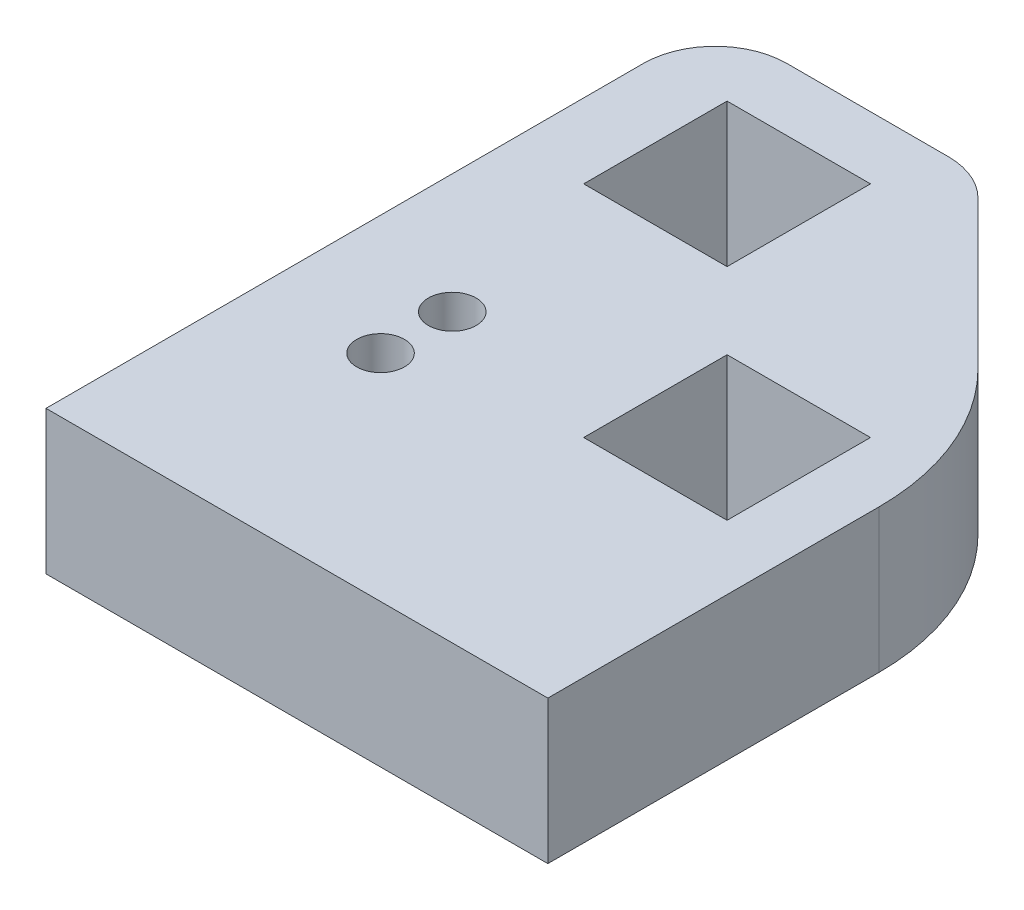
SolidWorks part; units mm, degrees
ref_plane "Front Plane" through (0, 0, 0) normal (0, 0, 1) x (1, 0, 0)
ref_plane "Top Plane" through (0, 0, 0) normal (0, 1, 0) x (1, 0, 0)
ref_plane "Right Plane" through (0, 0, 0) normal (1, 0, 0) x (0, 0, -1)
sketch "Sketch1" plane through (0, 0, 0) normal (0, 1, 0) x (1, 0, 0)
  line L0 (21, 0) -> (21, 9)
  line L1 (0, 0) -> (21, 0)
  line L2 (0, 0) -> (0, 28)
  line L3 (0, 28) -> (27, 28)
  line L4 (27, 9) -> (27, 28)
  line L5 (21, 9) -> (27, 9)
  dimension "D1" = 27
  dimension "D2" = 28
  dimension "D3" = 6
  dimension "D4" = 9
extrude "Boss-Extrude1" add sketch "Sketch1" along normal blind 6
sketch "Sketch2" plane through (0, 6, 0) normal (0, 1, 0) x (1, 0, 0)
  line L0 (-6.0122, 34.5122) -> (24, 4.5) construction
  line L1 (0, 0) -> (21, 0) construction
  line L2 (21, 0) -> (21, 9) construction
  line L4 (3.1152, 25.3848) -> (8.1152, 25.3848)
  line L5 (3.1152, 25.3848) -> (3.1152, 20.3848)
  line L6 (3.1152, 20.3848) -> (8.1152, 20.3848)
  line L7 (8.1152, 25.3848) -> (8.1152, 20.3848)
  line L8 (3.1152, 25.3848) -> (8.1152, 20.3848) construction
  line L9 (3.1152, 20.3848) -> (8.1152, 25.3848) construction
  line L10 (12.3076, 16.1924) -> (17.3076, 16.1924)
  line L11 (12.3076, 16.1924) -> (12.3076, 11.1924)
  line L12 (12.3076, 11.1924) -> (17.3076, 11.1924)
  line L13 (17.3076, 16.1924) -> (17.3076, 11.1924)
  line L14 (12.3076, 16.1924) -> (17.3076, 11.1924) construction
  line L15 (12.3076, 11.1924) -> (17.3076, 16.1924) construction
  point P6 (5.6152, 22.8848)
  point P11 (14.8076, 13.6924)
  dimension "D1" = 45
  dimension "D2" = 4.5
  dimension "D3" = 3
  dimension "D4" = 13
  dimension "D5" = 13
  dimension "D6" = 5
  dimension "D7" = 5
extrude "Cut-Extrude1" cut sketch "Sketch2" against normal through all
sketch "Sketch3" plane through (0, 6, 0) normal (0, 1, 0) x (1, 0, 0)
  line L0 (21, 18) -> (11, 28)
  line L1 (27, 28) -> (0, 28) construction
  line L2 (11, 28) -> (33.4367, 34.251)
  line L3 (33.4367, 34.251) -> (36.0805, 3.3835)
  line L4 (36.0805, 3.3835) -> (21, 9)
  line L5 (21, 9) -> (21, 18)
  dimension "D1" = 135
  dimension "D2" = 9
extrude "Cut-Extrude2" cut sketch "Sketch3" against normal through all
sketch "Sketch6" plane through (0, 6, 0) normal (0, 1, 0) x (1, 0, 0)
  line L1 (3.1152, 25.3848) -> (9.1152, 25.3848)
  line L2 (3.1152, 25.3848) -> (3.1152, 19.3848)
  line L3 (3.1152, 19.3848) -> (9.1152, 19.3848)
  line L4 (9.1152, 25.3848) -> (9.1152, 19.3848)
  line L5 (12.3076, 16.1924) -> (18.3076, 16.1924)
  line L6 (12.3076, 16.1924) -> (12.3076, 10.1924)
  line L7 (12.3076, 10.1924) -> (18.3076, 10.1924)
  line L8 (18.3076, 16.1924) -> (18.3076, 10.1924)
  dimension "D1" = 6
  dimension "D2" = 6
  dimension "D3" = 6
  dimension "D4" = 6
extrude "Cut-Extrude5" cut sketch "Sketch6" against normal through all
fillet "Fillet1" radius 10 1 edges at (21, 3, -18)
fillet "Fillet2" radius 3 2 edges at (11, 3, -28) (0, 3, -28)
sketch "Sketch5" plane through (0, 6, 0) normal (0, 1, 0) x (1, 0, 0)
  line L0 (0, 0) -> (21, 0) construction
  line L1 (0, 25) -> (0, 0) construction
  circle A0 centre (5, 12) radius 1
  circle A1 centre (5, 9) radius 1
  dimension "D1" = 2
  dimension "D2" = 2
  dimension "D3" = 3
  dimension "D4" = 9
  dimension "D5" = 5
extrude "Cut-Extrude3" cut sketch "Sketch5" against normal through all
